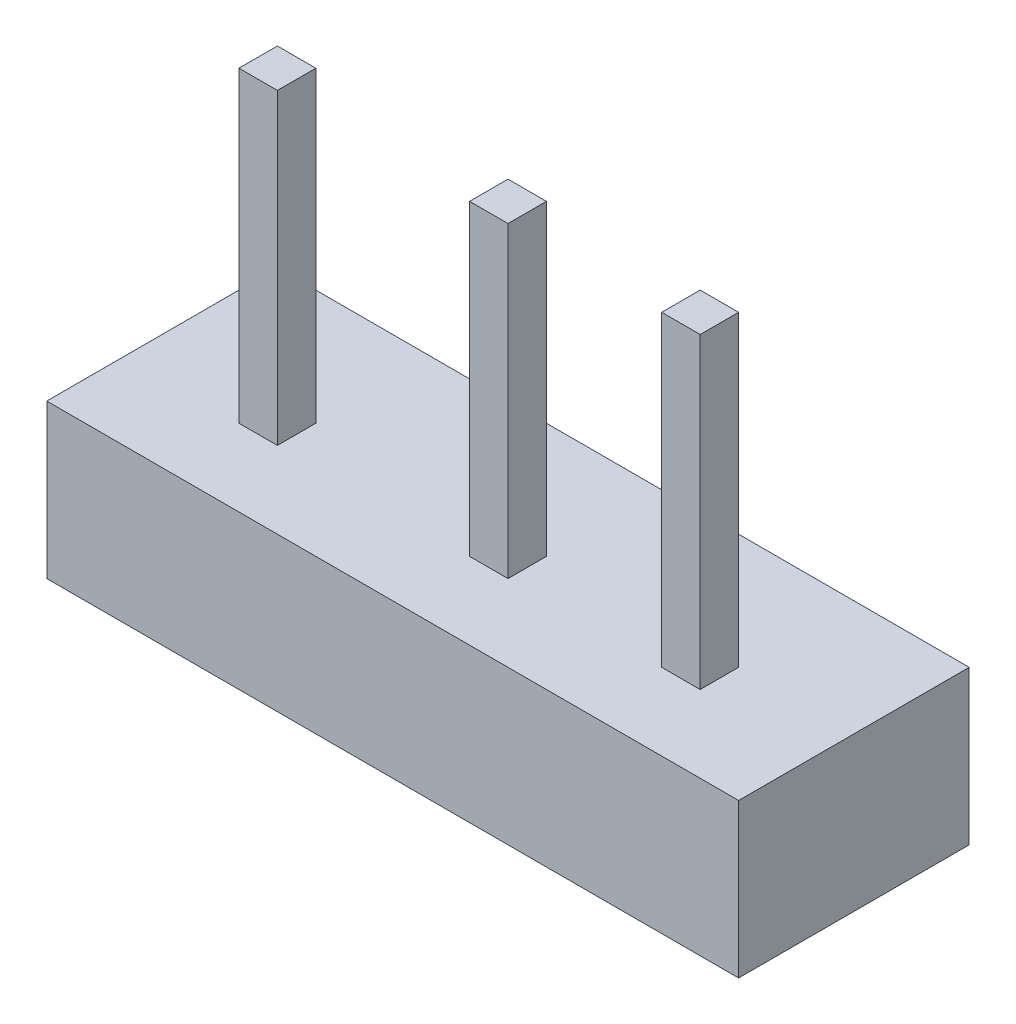
SolidWorks part; units mm, degrees
ref_plane "Front Plane" through (0, 0, 0) normal (0, 0, 1) x (1, 0, 0)
ref_plane "Top Plane" through (0, 0, 0) normal (0, 1, 0) x (1, 0, 0)
ref_plane "Right Plane" through (0, 0, 0) normal (1, 0, 0) x (0, 0, -1)
sketch "Sketch1" plane through (0, 0, 0) normal (0, 1, 0) x (1, 0, 0)
  line L1 (0, 0) -> (9, 0)
  line L2 (0, 0) -> (0, 3)
  line L3 (0, 3) -> (9, 3)
  line L4 (9, 0) -> (9, 3)
  dimension "D1" = 9
  dimension "D2" = 3
extrude "Boss-Extrude2" add sketch "Sketch1" along normal blind 2
sketch "Sketch2" plane through (0, 2, 0) normal (0, 1, 0) x (1, 0, 0)
  line L0 (9, 0) -> (9, 3) construction
  line L1 (7.5, 1.5) -> (7, 1.5)
  line L2 (7.5, 1.5) -> (7.5, 1)
  line L3 (7.5, 1) -> (7, 1)
  line L4 (7, 1.5) -> (7, 1)
  line L5 (5, 1.5) -> (4.5, 1.5)
  line L6 (5, 1.5) -> (5, 1)
  line L7 (5, 1) -> (4.5, 1)
  line L8 (4.5, 1.5) -> (4.5, 1)
  line L9 (2, 1.5) -> (1.5, 1.5)
  line L10 (2, 1.5) -> (2, 1)
  line L11 (2, 1) -> (1.5, 1)
  line L12 (1.5, 1.5) -> (1.5, 1)
  line L13 (0, 3) -> (0, 0) construction
  line L14 (9, 3) -> (0, 3) construction
  dimension "D1" = 0.5
  dimension "D2" = 0.5
  dimension "D3" = 0.5
  dimension "D4" = 0.5
  dimension "D5" = 0.5
  dimension "D6" = 0.5
  dimension "D7" = 1.5
  dimension "D9" = 1.5
  dimension "D10" = 2.5
  dimension "D11" = 1.5
  dimension "D12" = 1.5
  dimension "D13" = 1.5
extrude "Boss-Extrude3" add sketch "Sketch2" along normal blind 4 contours L10 L9 L12 L11 | L6 L5 L8 L7 | L2 L1 L4 L3
